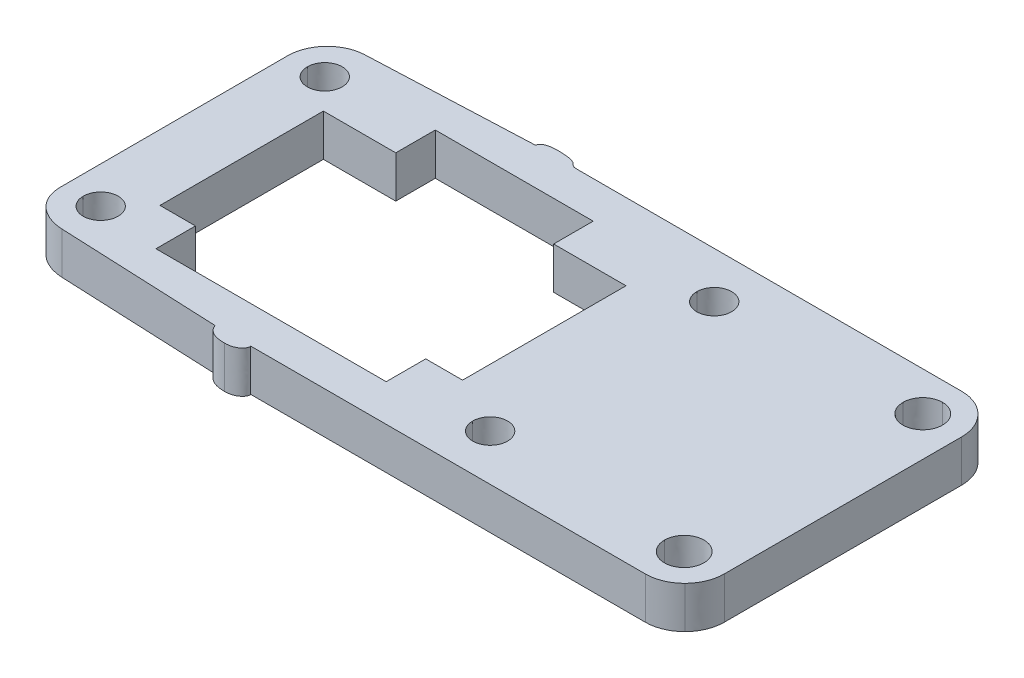
SolidWorks part; units mm, degrees
material "Acrylic (Medium-high impact)"
ref_plane "Front Plane" through (0, 0, 0) normal (0, 0, 1) x (1, 0, 0)
ref_plane "Top Plane" through (0, 0, 0) normal (0, 1, 0) x (1, 0, 0)
ref_plane "Right Plane" through (0, 0, 0) normal (1, 0, 0) x (0, 0, -1)
sketch "Sketch1" plane through (0, 0, 0) normal (0, 1, 0) x (1, 0, 0)
  line L15 (-0.3507, -7.768) -> (-0.4007, -7.768)
  line L16 (-0.4007, -7.768) -> (-0.4007, -10.7681)
  line L17 (-0.4007, -10.7681) -> (-17.8696, -10.7681)
  line L18 (-17.8696, -10.7681) -> (-17.8696, -7.768)
  line L19 (-17.8696, -7.768) -> (-20.5648, -7.768)
  line L20 (-20.5648, -7.768) -> (-20.5648, 4.6324)
  line L21 (-20.5648, 4.6324) -> (-15.0747, 4.6324)
  line L22 (-15.0747, 4.6324) -> (-15.0747, 7.6325)
  line L23 (-15.0747, 7.6325) -> (-3.0957, 7.6325)
  line L24 (-3.0957, 7.6325) -> (-3.0957, 4.6324)
  line L25 (-3.0957, 4.6324) -> (2.3944, 4.6324)
  line L26 (2.3944, 4.6324) -> (2.3944, -7.768)
  line L27 (2.3944, -7.768) -> (-0.3507, -7.768)
  line L28 (-7.9166, -13.5681) -> (22.0595, -13.5681)
  line L29 (25.0542, -10.5682) -> (25.0542, 7.4324)
  line L30 (-10.2758, 10.4325) -> (-22.7181, 9.9002)
  line L31 (-25.556, 6.9042) -> (-25.542, -10.3323)
  line L32 (-22.7181, -13.0358) -> (-10.5663, -13.5681)
  spline S0 degree 3 poles (-21.4384, -10.0682) (-21.4384, -9.3363) (-22.0306, -8.7432) (-22.761, -8.7432) (-23.4915, -8.7432) (-24.0838, -9.3363) (-24.0838, -10.0682) knots 2 2 2 2 3 3 3 4 4 4 4
  spline S1 degree 3 poles (-24.0838, -10.0682) (-24.0838, -10.7999) (-23.4915, -11.3932) (-22.7611, -11.3932) (-22.0306, -11.3932) (-21.4384, -10.7999) (-21.4384, -10.0682) knots 0 0 0 0 1 1 1 2 2 2 2
  spline S2 degree 3 poles (-21.4384, 6.9324) (-21.4384, 7.6643) (-22.0306, 8.2573) (-22.761, 8.2573) (-23.4915, 8.2573) (-24.0838, 7.6643) (-24.0838, 6.9324) knots 2 2 2 2 3 3 3 4 4 4 4
  spline S3 degree 3 poles (-24.0838, 6.9324) (-24.0838, 6.2006) (-23.4915, 5.6074) (-22.7611, 5.6074) (-22.0306, 5.6074) (-21.4384, 6.2006) (-21.4384, 6.9324) knots 0 0 0 0 1 1 1 2 2 2 2
  spline S4 degree 3 poles (-10.5663, -13.5681) (-10.5661, -13.5681) (-10.4437, -14.3648) (-9.0853, -14.3648) knots 0 0 0 0 1 1 1 1
  spline S5 degree 3 poles (-9.0853, -14.3648) (-7.9733, -14.3648) (-7.7476, -13.5681) (-7.9166, -13.5681) knots 1 1 1 1 2 2 2 2
  spline S6 degree 3 poles (22.0595, -13.5681) (22.8537, -13.5681) (23.6154, -13.2522) (24.177, -12.6896) knots 3 3 3 3 4 4 4 4
  spline S7 degree 3 poles (24.177, -12.6896) (24.7386, -12.127) (25.0542, -11.3637) (25.0542, -10.5682) knots 4 4 4 4 5 5 5 5
  spline S8 degree 3 poles (25.0542, 7.4324) (25.0542, 8.2282) (24.7386, 8.9912) (24.177, 9.5538) knots 6 6 6 6 7 7 7 7
  spline S9 degree 3 poles (24.177, 9.5538) (23.6154, 10.1165) (22.8537, 10.4325) (22.0595, 10.4325) knots 7 7 7 7 8 8 8 8
  spline S10 degree 2 poles (22.0595, 10.4325) (0.9302, 10.4325) (-7.1683, 10.4325) knots 8 8 8 9 9 9
  spline S11 degree 3 poles (-7.1683, 10.4325) (-7.8148, 10.4325) (-7.2355, 10.9365) (-9.0853, 10.9365) knots 9 9 9 9 10 10 10 10
  spline S12 degree 2 poles (-9.0853, 10.9365) (-10.1954, 10.9365) (-10.2758, 10.4325) knots 10 10 10 11 11 11
  spline S13 degree 3 poles (-22.7181, 9.9002) (-24.3088, 9.8167) (-25.556, 8.5001) (-25.556, 6.9042) knots 12 12 12 12 13 13 13 13
  spline S14 degree 3 poles (-25.542, -10.3323) (-25.542, -11.9282) (-24.3088, -12.9524) (-22.7181, -13.0358) knots 14 14 14 14 15 15 15 15
  spline S15 degree 3 poles (22.0595, 8.9827) (21.2324, 8.9827) (20.562, 8.3108) (20.562, 7.4824) knots 3 3 3 3 4 4 4 4
  spline S16 degree 3 poles (22.0593, 5.9824) (22.8862, 5.9822) (23.5569, 6.654) (23.5569, 7.4824) (23.5569, 8.3108) (22.8862, 8.9825) (22.0595, 8.9827) knots 1 1 1 1 2 2 2 3 3 3 3
  spline S17 degree 3 poles (20.562, 7.4824) (20.562, 6.654) (21.2324, 5.9824) (22.0593, 5.9824) knots 0 0 0 0 1 1 1 1
  spline S18 degree 3 poles (23.5567, -10.6183) (23.5569, -9.7897) (22.8862, -9.1182) (22.0595, -9.1182) (21.2324, -9.1182) (20.5622, -9.7897) (20.5622, -10.6181) knots 2 2 2 2 3 3 3 4 4 4 4
  spline S19 degree 3 poles (20.5622, -10.6181) (20.5622, -11.4465) (21.2324, -12.1181) (22.0593, -12.1181) (22.8862, -12.1181) (23.5567, -11.4465) (23.5567, -10.6183) knots 0 0 0 0 1 1 1 2 2 2 2
  spline S20 degree 3 poles (8.1091, -10.0683) (8.1091, -9.3365) (7.5169, -8.7432) (6.7865, -8.7432) (6.0559, -8.7432) (5.4637, -9.3365) (5.4637, -10.0682) knots 2 2 2 2 3 3 3 4 4 4 4
  spline S21 degree 3 poles (5.4637, -10.0682) (5.4637, -10.8) (6.0559, -11.3933) (6.7863, -11.3933) (7.5169, -11.3933) (8.1091, -10.8) (8.1091, -10.0683) knots 0 0 0 0 1 1 1 2 2 2 2
  spline S22 degree 3 poles (8.1091, 6.9322) (8.1091, 7.6641) (7.5169, 8.2573) (6.7865, 8.2573) (6.0559, 8.2573) (5.4637, 7.6641) (5.4637, 6.9324) knots 2 2 2 2 3 3 3 4 4 4 4
  spline S23 degree 3 poles (5.4637, 6.9324) (5.4637, 6.2005) (6.0559, 5.6072) (6.7863, 5.6072) (7.5169, 5.6072) (8.1091, 6.2005) (8.1091, 6.9322) knots 0 0 0 0 1 1 1 2 2 2 2
extrude "Boss-Extrude1" add sketch "Sketch1" along normal blind 3.175
